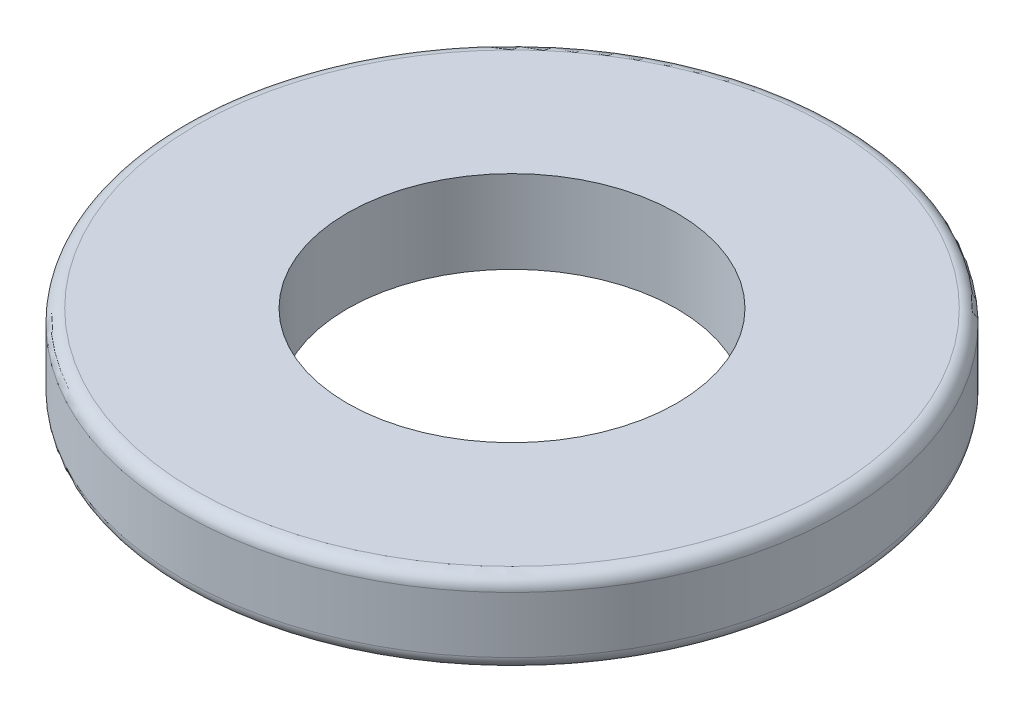
SolidWorks part; units mm, degrees
material "ABS"
ref_plane "Front Plane" through (0, 0, 0) normal (0, 0, 1) x (1, 0, 0)
ref_plane "Top Plane" through (0, 0, 0) normal (0, 1, 0) x (1, 0, 0)
ref_plane "Right Plane" through (0, 0, 0) normal (1, 0, 0) x (0, 0, -1)
sketch "Sketch1" plane through (0, 0, 0) normal (0, 1, 0) x (1, 0, 0)
  circle A0 centre (0, 0) radius 6.3119
  circle A1 centre (0, 0) radius 3.156
  dimension "D1" = 6.3119
  dimension "D2" = 12.6238
extrude "Boss-Extrude1" add sketch "Sketch1" along normal blind 1.5875
fillet "Fillet1" radius 0.254 2 edges at (0, 0, 6.3119) (0, 1.5875, 6.3119)
